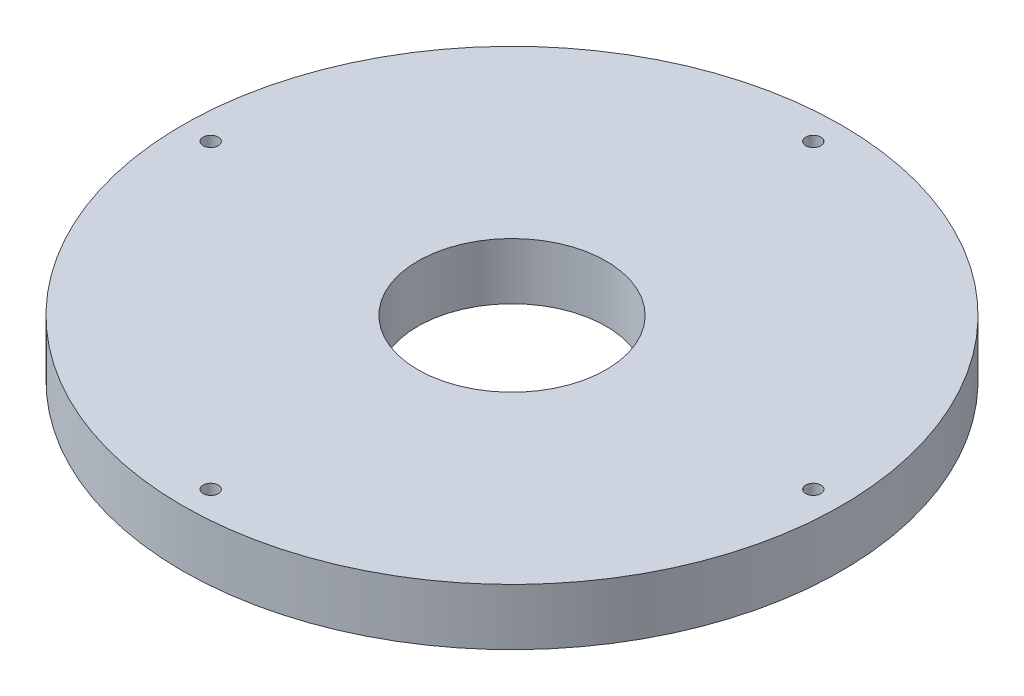
SolidWorks part; units mm, degrees
material "Oak"
ref_plane "Front Plane" through (0, 0, 0) normal (0, 0, 1) x (1, 0, 0)
ref_plane "Top Plane" through (0, 0, 0) normal (0, 1, 0) x (1, 0, 0)
ref_plane "Right Plane" through (0, 0, 0) normal (1, 0, 0) x (0, 0, -1)
sketch "Sketch2" plane through (0, 0, 0) normal (0, 1, 0) x (1, 0, 0)
  circle A0 centre (0, 0) radius 175
  dimension "D1" = 350
extrude "Boss-Extrude1" add sketch "Sketch2" along normal mid plane 30
sketch "Sketch3" plane through (0, 15, 0) normal (0, 1, 0) x (1, 0, 0)
  line L0 (0, -1000) -> (0, 49000) construction
  line L1 (-1000, 0) -> (49000, 0) construction
  circle A0 centre (0, 160) radius 4
  circle A1 centre (0, -160) radius 4
  circle A2 centre (-160, 0) radius 4
  circle A3 centre (160, 0) radius 4
  circle A4 centre (0, 0) radius 50
  point P7 (0, -160)
  dimension "D1" = 8
  dimension "D3" = 8
  dimension "D4" = 160
  dimension "D5" = 100
  dimension "D2" = 160
extrude "Cut-Extrude1" cut sketch "Sketch3" against normal blind 30
